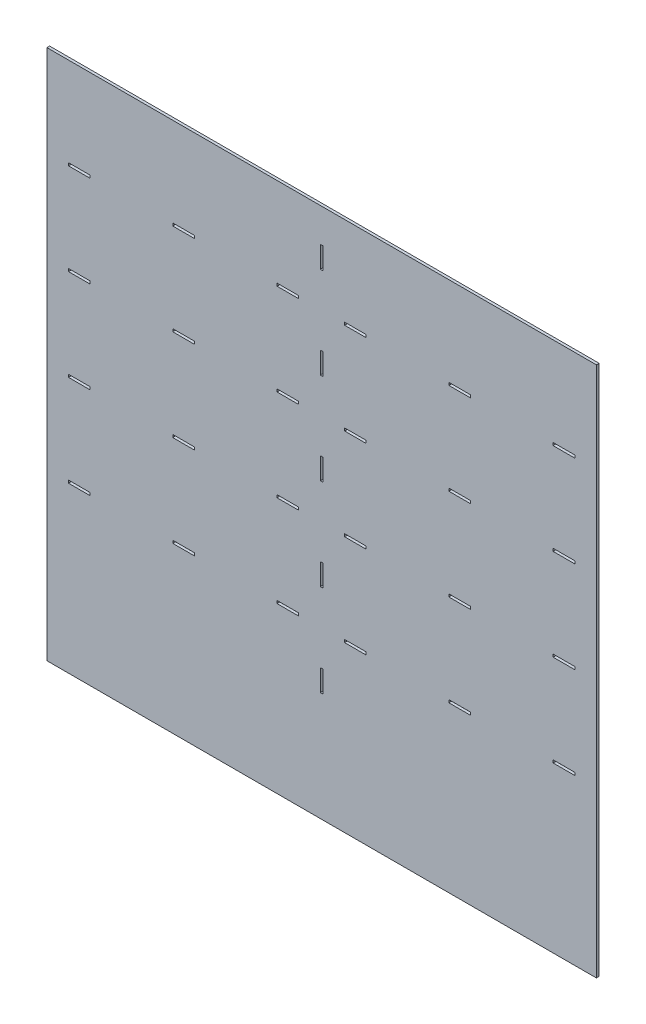
SolidWorks part; units mm, degrees
material "6061-T6 (SS)"
ref_plane "X-Y Datum" through (0, 0, 0) normal (0, 0, 1) x (1, 0, 0)
ref_plane "X-Z Datum" through (0, 0, 0) normal (0, 1, 0) x (1, 0, 0)
ref_plane "Y-Z Datum" through (0, 0, 0) normal (1, 0, 0) x (0, 0, -1)
sketch "Sketch1" plane through (0, 0, 0) normal (0, 0, 1) x (1, 0, 0)
  line L1 (0, 0) -> (314.2742, 0)
  line L2 (0, 0) -> (0, 86.4667)
  line L3 (0, 86.4667) -> (314.2742, 86.4667)
  line L4 (314.2742, 0) -> (314.2742, 86.4667)
  line L5 (0, 86.4667) -> (314.2742, 86.4667)
  line L6 (0, 86.4667) -> (0, 87.7367)
  line L7 (0, 87.7367) -> (314.2742, 87.7367)
  line L8 (314.2742, 86.4667) -> (314.2742, 87.7367)
  line L9 (0, 0) -> (314.2742, 0)
  line L10 (0, 0) -> (0, -1.27)
  line L11 (0, -1.27) -> (314.2742, -1.27)
  line L12 (314.2742, 0) -> (314.2742, -1.27)
  line L13 (0, 87.7367) -> (-1.27, 87.7367)
  line L14 (0, 87.7367) -> (0, -1.27)
  line L15 (0, -1.27) -> (-1.27, -1.27)
  line L16 (-1.27, 87.7367) -> (-1.27, -1.27)
  line L17 (314.2742, 87.7367) -> (315.5442, 87.7367)
  line L18 (314.2742, 87.7367) -> (314.2742, -1.27)
  line L19 (314.2742, -1.27) -> (315.5442, -1.27)
  line L20 (315.5442, 87.7367) -> (315.5442, -1.27)
  line L21 (-1.27, 87.7367) -> (-4.445, 87.7367)
  line L22 (-1.27, 87.7367) -> (-1.27, -1.27)
  line L23 (-1.27, -1.27) -> (-4.445, -1.27)
  line L24 (-4.445, 87.7367) -> (-4.445, -1.27)
  line L25 (-4.445, 87.7367) -> (-7.62, 87.7367)
  line L26 (-4.445, 87.7367) -> (-4.445, -1.27)
  line L27 (-4.445, -1.27) -> (-7.62, -1.27)
  line L28 (-7.62, 87.7367) -> (-7.62, -1.27)
  line L29 (315.5442, 87.7367) -> (318.7192, 87.7367)
  line L30 (315.5442, 87.7367) -> (315.5442, -1.27)
  line L31 (315.5442, -1.27) -> (318.7192, -1.27)
  line L32 (318.7192, 87.7367) -> (318.7192, -1.27)
  line L33 (318.7192, 87.7367) -> (321.8942, 87.7367)
  line L34 (318.7192, 87.7367) -> (318.7192, -1.27)
  line L35 (318.7192, -1.27) -> (321.8942, -1.27)
  line L36 (321.8942, 87.7367) -> (321.8942, -1.27)
  line L37 (-7.62, 87.7367) -> (321.8942, 87.7367)
  line L38 (-7.62, 87.7367) -> (-7.62, 90.9117)
  line L39 (-7.62, 90.9117) -> (321.8942, 90.9117)
  line L40 (321.8942, 87.7367) -> (321.8942, 90.9117)
  line L41 (-7.62, 90.9117) -> (321.8942, 90.9117)
  line L42 (-7.62, 90.9117) -> (-7.62, 94.0867)
  line L43 (-7.62, 94.0867) -> (321.8942, 94.0867)
  line L44 (321.8942, 90.9117) -> (321.8942, 94.0867)
  line L45 (-7.62, -1.27) -> (321.8942, -1.27)
  line L46 (-7.62, -1.27) -> (-7.62, -4.445)
  line L47 (-7.62, -4.445) -> (321.8942, -4.445)
  line L48 (321.8942, -1.27) -> (321.8942, -4.445)
  line L49 (321.8942, -4.445) -> (-7.62, -4.445)
  line L50 (321.8942, -4.445) -> (321.8942, -7.62)
  line L51 (321.8942, -7.62) -> (-7.62, -7.62)
  line L52 (-7.62, -4.445) -> (-7.62, -7.62)
  dimension "D1" = 314.2742
  dimension "D2" = 86.4667
  dimension "D3" = 1.27
  dimension "D4" = 1.27
  dimension "D5" = 1.27
  dimension "D6" = 1.27
  dimension "D7" = 3.175
  dimension "D8" = 3.175
  dimension "D9" = 3.175
  dimension "D10" = 3.175
  dimension "D11" = 3.175
  dimension "D12" = 3.175
  dimension "D13" = 3.175
  dimension "D14" = 3.175
sketch "Sketch4" plane through (0, 0, 0) normal (0, 0, 1) x (1, 0, 0)
  line L0 (-4.445, 87.7367) -> (-4.445, 90.9117) construction
  line L1 (-1.27, 87.7367) -> (315.5442, 87.7367)
  line L2 (-1.27, 87.7367) -> (-1.27, -1.27)
  line L3 (-1.27, -1.27) -> (315.5442, -1.27)
  line L4 (315.5442, 87.7367) -> (315.5442, -1.27)
  line L5 (-7.62, 90.9117) -> (321.8942, 90.9117) construction
  line L6 (318.7192, -1.27) -> (318.7192, -4.445) construction
  line L7 (-7.62, -4.445) -> (321.8942, -4.445) construction
  line L8 (-7.62, 92.4992) -> (-3.4571, 92.4992) construction
  line L9 (-4.445, 90.9117) -> (318.7192, 90.9117)
  line L10 (-4.445, 90.9117) -> (-4.445, -4.445)
  line L11 (-4.445, -4.445) -> (318.7192, -4.445)
  line L12 (318.7192, 90.9117) -> (318.7192, -4.445)
  line L14 (-1.27, 186.2684) -> (315.5442, 186.2684)
  line L15 (315.5442, 97.2617) -> (315.5442, 186.2684)
  line L16 (-1.27, 97.2617) -> (315.5442, 97.2617)
  line L17 (-1.27, 97.2617) -> (-1.27, 186.2684)
  line L18 (-4.445, 189.4434) -> (318.7192, 189.4434)
  line L19 (318.7192, 94.0867) -> (318.7192, 189.4434)
  line L20 (-4.445, 94.0867) -> (318.7192, 94.0867)
  line L21 (-4.445, 94.0867) -> (-4.445, 189.4434)
  line L22 (-4.445, 189.4434) -> (-4.445, 191.0309) construction
  line L23 (-4.445, 191.0309) -> (2.0975, 191.0309) construction
  line L24 (-1.27, 284.8) -> (-1.27, 195.7934)
  line L25 (-1.27, 284.8) -> (315.5442, 284.8)
  line L26 (315.5442, 284.8) -> (315.5442, 195.7934)
  line L27 (-1.27, 195.7934) -> (315.5442, 195.7934)
  line L28 (-4.445, 287.975) -> (-4.445, 192.6184)
  line L29 (-4.445, 287.975) -> (318.7192, 287.975)
  line L30 (318.7192, 287.975) -> (318.7192, 192.6184)
  line L31 (-4.445, 192.6184) -> (318.7192, 192.6184)
  line L32 (-4.445, 287.975) -> (-4.445, 289.5625) construction
  line L33 (-4.445, 289.5625) -> (-1.5046, 289.5625) construction
  line L34 (-1.27, 294.325) -> (315.5442, 294.325)
  line L35 (315.5442, 294.325) -> (315.5442, 383.3317)
  line L36 (-1.27, 383.3317) -> (315.5442, 383.3317)
  line L37 (-1.27, 294.325) -> (-1.27, 383.3317)
  line L38 (-4.445, 291.15) -> (318.7192, 291.15)
  line L39 (318.7192, 291.15) -> (318.7192, 386.5067)
  line L40 (-4.445, 386.5067) -> (318.7192, 386.5067)
  line L41 (-4.445, 291.15) -> (-4.445, 386.5067)
  line L42 (-4.445, 386.5067) -> (-4.445, 388.0942) construction
  line L43 (-4.445, 388.0942) -> (54.1144, 388.0942) construction
  line L44 (-1.27, 481.8634) -> (-1.27, 392.8567)
  line L45 (-1.27, 392.8567) -> (315.5442, 392.8567)
  line L46 (315.5442, 481.8634) -> (315.5442, 392.8567)
  line L47 (-1.27, 481.8634) -> (315.5442, 481.8634)
  line L48 (-4.445, 485.0384) -> (-4.445, 389.6817)
  line L49 (-4.445, 389.6817) -> (318.7192, 389.6817)
  line L50 (318.7192, 485.0384) -> (318.7192, 389.6817)
  line L51 (-4.445, 485.0384) -> (318.7192, 485.0384)
  line L52 (318.7192, -4.445) -> (320.3067, -4.445) construction
  line L53 (320.3067, -4.445) -> (320.3067, 0.7988) construction
  line L54 (641.8834, -1.27) -> (325.0692, -1.27)
  line L55 (325.0692, 87.7367) -> (325.0692, -1.27)
  line L56 (641.8834, 87.7367) -> (325.0692, 87.7367)
  line L57 (641.8834, 87.7367) -> (641.8834, -1.27)
  line L58 (645.0584, -4.445) -> (321.8942, -4.445)
  line L59 (321.8942, 90.9117) -> (321.8942, -4.445)
  line L60 (645.0584, 90.9117) -> (321.8942, 90.9117)
  line L61 (645.0584, 90.9117) -> (645.0584, -4.445)
  line L62 (641.8834, 97.2617) -> (641.8834, 186.2684)
  line L63 (641.8834, 97.2617) -> (325.0692, 97.2617)
  line L64 (325.0692, 97.2617) -> (325.0692, 186.2684)
  line L65 (641.8834, 186.2684) -> (325.0692, 186.2684)
  line L66 (645.0584, 94.0867) -> (645.0584, 189.4434)
  line L67 (645.0584, 94.0867) -> (321.8942, 94.0867)
  line L68 (321.8942, 94.0867) -> (321.8942, 189.4434)
  line L69 (645.0584, 189.4434) -> (321.8942, 189.4434)
  line L70 (641.8834, 284.8) -> (325.0692, 284.8)
  line L71 (325.0692, 284.8) -> (325.0692, 195.7934)
  line L72 (641.8834, 195.7934) -> (325.0692, 195.7934)
  line L73 (641.8834, 284.8) -> (641.8834, 195.7934)
  line L74 (645.0584, 287.975) -> (321.8942, 287.975)
  line L75 (321.8942, 287.975) -> (321.8942, 192.6184)
  line L76 (645.0584, 192.6184) -> (321.8942, 192.6184)
  line L77 (645.0584, 287.975) -> (645.0584, 192.6184)
  line L78 (641.8834, 294.325) -> (641.8834, 383.3317)
  line L79 (641.8834, 383.3317) -> (325.0692, 383.3317)
  line L80 (325.0692, 294.325) -> (325.0692, 383.3317)
  line L81 (641.8834, 294.325) -> (325.0692, 294.325)
  line L82 (645.0584, 291.15) -> (645.0584, 386.5067)
  line L83 (645.0584, 386.5067) -> (321.8942, 386.5067)
  line L84 (321.8942, 291.15) -> (321.8942, 386.5067)
  line L85 (645.0584, 291.15) -> (321.8942, 291.15)
  line L86 (641.8834, 481.8634) -> (325.0692, 481.8634)
  line L87 (325.0692, 481.8634) -> (325.0692, 392.8567)
  line L88 (641.8834, 392.8567) -> (325.0692, 392.8567)
  line L89 (641.8834, 481.8634) -> (641.8834, 392.8567)
  line L90 (645.0584, 485.0384) -> (321.8942, 485.0384)
  line L91 (321.8942, 485.0384) -> (321.8942, 389.6817)
  line L92 (645.0584, 389.6817) -> (321.8942, 389.6817)
  line L93 (645.0584, 485.0384) -> (645.0584, 389.6817)
sketch "Sketch5" plane through (0, 0, 0) normal (0, 0, 1) x (1, 0, 0)
  line L1 (-4.445, -4.445) -> (645.0584, -4.445)
  line L2 (-4.445, -4.445) -> (-4.445, 485.0384)
  line L3 (-4.445, 485.0384) -> (645.0584, 485.0384)
  line L4 (645.0584, -4.445) -> (645.0584, 485.0384)
  line L17 (-4.445, 240.2967) -> (411.848, 240.2967) construction
  line L18 (320.3067, -200004.445) -> (320.3067, 200000.7988) construction
  line L19 (318.7192, 227.5967) -> (321.8942, 227.5967)
  line L20 (318.7192, 227.5967) -> (318.7192, 252.9967)
  line L21 (318.7192, 252.9967) -> (321.8942, 252.9967)
  line L22 (321.8942, 227.5967) -> (321.8942, 252.9967)
  line L23 (318.7192, 227.5967) -> (321.8942, 252.9967) construction
  line L24 (318.7192, 252.9967) -> (321.8942, 227.5967) construction
  line L25 (321.8942, 287.975) -> (321.8942, 192.6184) construction
  line L26 (315.5442, 481.8634) -> (315.5442, 392.8567) construction
  line L27 (321.8942, 485.0384) -> (321.8942, 389.6817) construction
  line L28 (318.7192, 424.6601) -> (321.8942, 424.6601)
  line L29 (318.7192, 424.6601) -> (318.7192, 450.0601)
  line L30 (318.7192, 450.0601) -> (321.8942, 450.0601)
  line L31 (321.8942, 424.6601) -> (321.8942, 450.0601)
  line L32 (318.7192, 424.6601) -> (321.8942, 450.0601) construction
  line L33 (318.7192, 450.0601) -> (321.8942, 424.6601) construction
  line L34 (315.5442, 383.3317) -> (315.5442, 294.325) construction
  line L35 (321.8942, 291.15) -> (321.8942, 386.5067) construction
  line L36 (318.7192, 326.1284) -> (321.8942, 326.1284)
  line L37 (318.7192, 326.1284) -> (318.7192, 351.5284)
  line L38 (318.7192, 351.5284) -> (321.8942, 351.5284)
  line L39 (321.8942, 326.1284) -> (321.8942, 351.5284)
  line L40 (318.7192, 326.1284) -> (321.8942, 351.5284) construction
  line L41 (318.7192, 351.5284) -> (321.8942, 326.1284) construction
  line L42 (315.5442, 186.2684) -> (315.5442, 97.2617) construction
  line L44 (321.8942, 94.0867) -> (321.8942, 189.4434) construction
  line L45 (318.7192, 129.065) -> (321.8942, 129.065)
  line L46 (318.7192, 129.065) -> (318.7192, 154.465)
  line L47 (318.7192, 154.465) -> (321.8942, 154.465)
  line L48 (321.8942, 129.065) -> (321.8942, 154.465)
  line L49 (318.7192, 129.065) -> (321.8942, 154.465) construction
  line L50 (318.7192, 154.465) -> (321.8942, 129.065) construction
  line L51 (315.5442, 87.7367) -> (315.5442, -1.27) construction
  line L52 (321.8942, 90.9117) -> (321.8942, -4.445) construction
  line L53 (318.7192, 30.5333) -> (321.8942, 30.5333)
  line L54 (318.7192, 30.5333) -> (318.7192, 55.9333)
  line L55 (318.7192, 55.9333) -> (321.8942, 55.9333)
  line L56 (321.8942, 30.5333) -> (321.8942, 55.9333)
  line L57 (318.7192, 30.5333) -> (321.8942, 55.9333) construction
  line L58 (318.7192, 55.9333) -> (321.8942, 30.5333) construction
  line L59 (-4.445, 389.6817) -> (318.7192, 389.6817) construction
  line L60 (20.955, 389.6817) -> (46.355, 389.6817)
  line L61 (20.955, 389.6817) -> (20.955, 386.5067)
  line L62 (20.955, 386.5067) -> (46.355, 386.5067)
  line L63 (46.355, 389.6817) -> (46.355, 386.5067)
  line L64 (-4.445, 386.5067) -> (318.7192, 386.5067) construction
  line L65 (157.1371, 481.8634) -> (157.1371, -33.5321) construction
  line L66 (-1.27, 481.8634) -> (315.5442, 481.8634) construction
  line L67 (-4.445, 291.15) -> (318.7192, 291.15) construction
  line L68 (20.955, 291.15) -> (46.355, 291.15)
  line L69 (20.955, 291.15) -> (20.955, 287.975)
  line L70 (20.955, 287.975) -> (46.355, 287.975)
  line L71 (46.355, 291.15) -> (46.355, 287.975)
  line L72 (-4.445, 287.975) -> (318.7192, 287.975) construction
  line L73 (-4.445, 192.6184) -> (318.7192, 192.6184) construction
  line L74 (20.955, 192.6184) -> (46.355, 192.6184)
  line L75 (20.955, 192.6184) -> (20.955, 189.4434)
  line L76 (20.955, 189.4434) -> (46.355, 189.4434)
  line L77 (46.355, 192.6184) -> (46.355, 189.4434)
  line L78 (-4.445, 189.4434) -> (318.7192, 189.4434) construction
  line L79 (-4.445, 94.0867) -> (318.7192, 94.0867) construction
  line L80 (20.955, 94.0867) -> (46.355, 94.0867)
  line L81 (20.955, 94.0867) -> (20.955, 90.9117)
  line L82 (20.955, 90.9117) -> (46.355, 90.9117)
  line L83 (46.355, 94.0867) -> (46.355, 90.9117)
  line L84 (-4.445, 90.9117) -> (318.7192, 90.9117) construction
  line L85 (293.3192, 90.9117) -> (267.9192, 90.9117)
  line L86 (267.9192, 94.0867) -> (267.9192, 90.9117)
  line L87 (293.3192, 94.0867) -> (267.9192, 94.0867)
  line L88 (293.3192, 94.0867) -> (293.3192, 90.9117)
  line L89 (293.3192, 189.4434) -> (267.9192, 189.4434)
  line L90 (267.9192, 192.6184) -> (267.9192, 189.4434)
  line L91 (293.3192, 192.6184) -> (267.9192, 192.6184)
  line L92 (293.3192, 192.6184) -> (293.3192, 189.4434)
  line L93 (293.3192, 287.975) -> (267.9192, 287.975)
  line L94 (267.9192, 291.15) -> (267.9192, 287.975)
  line L95 (293.3192, 291.15) -> (267.9192, 291.15)
  line L96 (293.3192, 291.15) -> (293.3192, 287.975)
  line L97 (293.3192, 386.5067) -> (267.9192, 386.5067)
  line L98 (267.9192, 389.6817) -> (267.9192, 386.5067)
  line L99 (293.3192, 389.6817) -> (267.9192, 389.6817)
  line L100 (293.3192, 389.6817) -> (293.3192, 386.5067)
  line L101 (-200004.445, 388.0942) -> (200054.1144, 388.0942) construction
  line L102 (144.4371, 386.5067) -> (169.8371, 386.5067)
  line L103 (144.4371, 386.5067) -> (144.4371, 389.6817)
  line L104 (144.4371, 389.6817) -> (169.8371, 389.6817)
  line L105 (169.8371, 386.5067) -> (169.8371, 389.6817)
  line L106 (144.4371, 386.5067) -> (169.8371, 389.6817) construction
  line L107 (144.4371, 389.6817) -> (169.8371, 386.5067) construction
  line L108 (-200007.62, 92.4992) -> (199996.5429, 92.4992) construction
  line L109 (144.4371, 287.9943) -> (169.8371, 287.9943)
  line L110 (144.4371, 287.9943) -> (144.4371, 291.15)
  line L111 (144.4371, 291.15) -> (169.8371, 291.15)
  line L112 (169.8371, 287.9943) -> (169.8371, 291.15)
  line L113 (144.4371, 287.9943) -> (169.8371, 291.15) construction
  line L114 (144.4371, 291.15) -> (169.8371, 287.9943) construction
  line L115 (144.4371, 189.7684) -> (169.8371, 189.7684)
  line L116 (144.4371, 189.7684) -> (144.4371, 192.6184)
  line L117 (144.4371, 192.6184) -> (169.8371, 192.6184)
  line L118 (169.8371, 189.7684) -> (169.8371, 192.6184)
  line L119 (144.4371, 189.7684) -> (169.8371, 192.6184) construction
  line L120 (144.4371, 192.6184) -> (169.8371, 189.7684) construction
  line L121 (144.4371, 90.0322) -> (169.8371, 90.0322)
  line L122 (144.4371, 90.0322) -> (144.4371, 94.9661)
  line L123 (144.4371, 94.9661) -> (169.8371, 94.9661)
  line L124 (169.8371, 90.0322) -> (169.8371, 94.9661)
  line L125 (144.4371, 90.0322) -> (169.8371, 94.9661) construction
  line L126 (144.4371, 94.9661) -> (169.8371, 90.0322) construction
  line L127 (320.3067, 527.3775) -> (320.3067, -150.1423) construction
  line L128 (619.6584, 90.9117) -> (594.2584, 90.9117)
  line L129 (594.2584, 94.0867) -> (594.2584, 90.9117)
  line L130 (619.6584, 94.0867) -> (594.2584, 94.0867)
  line L131 (619.6584, 94.0867) -> (619.6584, 90.9117)
  line L132 (496.1763, 94.9661) -> (470.7763, 94.9661)
  line L133 (470.7763, 90.0322) -> (470.7763, 94.9661)
  line L134 (496.1763, 90.0322) -> (470.7763, 90.0322)
  line L135 (496.1763, 90.0322) -> (496.1763, 94.9661)
  line L136 (347.2942, 94.0867) -> (347.2942, 90.9117)
  line L137 (347.2942, 94.0867) -> (372.6942, 94.0867)
  line L138 (372.6942, 94.0867) -> (372.6942, 90.9117)
  line L139 (347.2942, 90.9117) -> (372.6942, 90.9117)
  line L140 (347.2942, 192.6184) -> (347.2942, 189.4434)
  line L141 (347.2942, 192.6184) -> (372.6942, 192.6184)
  line L142 (372.6942, 192.6184) -> (372.6942, 189.4434)
  line L143 (347.2942, 189.4434) -> (372.6942, 189.4434)
  line L144 (496.1763, 192.6184) -> (470.7763, 192.6184)
  line L145 (470.7763, 189.7684) -> (470.7763, 192.6184)
  line L146 (496.1763, 189.7684) -> (470.7763, 189.7684)
  line L147 (496.1763, 189.7684) -> (496.1763, 192.6184)
  line L148 (619.6584, 189.4434) -> (594.2584, 189.4434)
  line L149 (594.2584, 192.6184) -> (594.2584, 189.4434)
  line L150 (619.6584, 192.6184) -> (594.2584, 192.6184)
  line L151 (619.6584, 192.6184) -> (619.6584, 189.4434)
  line L152 (619.6584, 287.975) -> (594.2584, 287.975)
  line L153 (594.2584, 291.15) -> (594.2584, 287.975)
  line L154 (619.6584, 291.15) -> (594.2584, 291.15)
  line L155 (619.6584, 291.15) -> (619.6584, 287.975)
  line L156 (496.1763, 291.15) -> (470.7763, 291.15)
  line L157 (470.7763, 287.9943) -> (470.7763, 291.15)
  line L158 (496.1763, 287.9943) -> (470.7763, 287.9943)
  line L159 (496.1763, 287.9943) -> (496.1763, 291.15)
  line L160 (347.2942, 291.15) -> (347.2942, 287.975)
  line L161 (347.2942, 291.15) -> (372.6942, 291.15)
  line L162 (372.6942, 291.15) -> (372.6942, 287.975)
  line L163 (347.2942, 287.975) -> (372.6942, 287.975)
  line L164 (347.2942, 389.6817) -> (347.2942, 386.5067)
  line L165 (347.2942, 389.6817) -> (372.6942, 389.6817)
  line L166 (372.6942, 389.6817) -> (372.6942, 386.5067)
  line L167 (347.2942, 386.5067) -> (372.6942, 386.5067)
  line L168 (496.1763, 389.6817) -> (470.7763, 389.6817)
  line L169 (470.7763, 386.5067) -> (470.7763, 389.6817)
  line L170 (496.1763, 386.5067) -> (470.7763, 386.5067)
  line L171 (496.1763, 386.5067) -> (496.1763, 389.6817)
  line L172 (619.6584, 386.5067) -> (594.2584, 386.5067)
  line L173 (594.2584, 389.6817) -> (594.2584, 386.5067)
  line L174 (619.6584, 389.6817) -> (594.2584, 389.6817)
  line L175 (619.6584, 389.6817) -> (619.6584, 386.5067)
  point P8 (320.3067, 43.2333)
  point P12 (320.3067, 437.3601)
  point P24 (320.3067, 240.2967)
  point P40 (320.3067, 338.8284)
  point P53 (320.3067, 141.765)
  point P113 (157.1371, 388.0942)
  point P120 (157.1371, 289.5722)
  point P125 (157.1371, 191.1934)
  point P130 (157.1371, 92.4992)
  dimension "D1" = 25.4
  dimension "D2" = 25.4
  dimension "D3" = 25.4
  dimension "D4" = 25.4
  dimension "D5" = 25.4
  dimension "D6" = 25.4
  dimension "D7" = 25.4
  dimension "D8" = 25.4
sketch "Sketch7" plane through (0, 0, 0) normal (0, 0, 1) x (1, 0, 0)
  line L0 (-2.032, 422.1632) -> (-2.032, 423.7507) construction
  line L5 (-2.032, -2.032) -> (-2.032, 96.0704)
  line L10 (0, 0) -> (310.8274, 0)
  line L11 (0, 0) -> (0, 94.0384)
  line L12 (0, 94.0384) -> (310.8274, 94.0384)
  line L13 (310.8274, 0) -> (310.8274, 94.0384)
  line L14 (-2.032, 96.0704) -> (312.8594, 96.0704)
  line L15 (312.8594, -2.032) -> (312.8594, 96.0704)
  line L16 (-2.032, -2.032) -> (312.8594, -2.032)
  line L17 (-5.207, 99.2454) -> (316.0344, 99.2454)
  line L18 (316.0344, -5.207) -> (316.0344, 99.2454)
  line L19 (-5.207, -5.207) -> (316.0344, -5.207)
  line L20 (-5.207, -5.207) -> (-5.207, 99.2454)
  line L21 (-5.207, 99.2454) -> (-5.207, 100.8507) construction
  line L22 (-5.207, 100.8507) -> (332.9978, 100.8507) construction
  line L23 (-2.032, 203.7334) -> (312.8594, 203.7334)
  line L24 (312.8594, 203.7334) -> (312.8594, 105.631)
  line L25 (-2.032, 105.631) -> (312.8594, 105.631)
  line L26 (-2.032, 203.7334) -> (-2.032, 105.631)
  line L27 (0, 107.663) -> (310.8274, 107.663)
  line L28 (310.8274, 201.7014) -> (310.8274, 107.663)
  line L29 (0, 201.7014) -> (310.8274, 201.7014)
  line L30 (0, 201.7014) -> (0, 107.663)
  line L31 (-5.207, 206.9084) -> (-5.207, 102.456)
  line L32 (-5.207, 206.9084) -> (316.0344, 206.9084)
  line L33 (316.0344, 206.9084) -> (316.0344, 102.456)
  line L34 (-5.207, 102.456) -> (316.0344, 102.456)
  line L35 (-5.207, 206.9084) -> (-5.207, 208.4959) construction
  line L36 (-5.207, 208.4959) -> (6.6362, 208.4959) construction
  line L37 (-2.032, 213.2584) -> (-2.032, 311.3608)
  line L38 (-2.032, 311.3608) -> (312.8594, 311.3608)
  line L39 (312.8594, 213.2584) -> (312.8594, 311.3608)
  line L40 (-2.032, 213.2584) -> (312.8594, 213.2584)
  line L41 (0, 215.2904) -> (0, 309.3288)
  line L42 (0, 215.2904) -> (310.8274, 215.2904)
  line L43 (310.8274, 215.2904) -> (310.8274, 309.3288)
  line L44 (0, 309.3288) -> (310.8274, 309.3288)
  line L45 (-5.207, 210.0834) -> (316.0344, 210.0834)
  line L46 (316.0344, 210.0834) -> (316.0344, 314.5358)
  line L47 (-5.207, 314.5358) -> (316.0344, 314.5358)
  line L48 (-5.207, 210.0834) -> (-5.207, 314.5358)
  line L49 (-3.3313, 314.5358) -> (-3.3313, 316.1233) construction
  line L50 (-8.425, 316.1233) -> (12.0376, 316.1233) construction
  line L51 (0, 416.9562) -> (310.8274, 416.9562)
  line L52 (310.8274, 416.9562) -> (310.8274, 322.9178)
  line L53 (0, 322.9178) -> (310.8274, 322.9178)
  line L54 (0, 416.9562) -> (0, 322.9178)
  line L55 (-2.032, 418.9882) -> (312.8594, 418.9882)
  line L56 (312.8594, 418.9882) -> (312.8594, 320.8858)
  line L57 (-2.032, 320.8858) -> (312.8594, 320.8858)
  line L58 (-2.032, 418.9882) -> (-2.032, 320.8858)
  line L59 (-5.207, 422.1632) -> (-5.207, 317.7108)
  line L60 (-5.207, 317.7108) -> (316.0344, 317.7108)
  line L61 (316.0344, 422.1632) -> (316.0344, 317.7108)
  line L62 (-5.207, 422.1632) -> (316.0344, 422.1632)
  line L63 (-10.8123, 423.7507) -> (13.1304, 423.7507) construction
  line L64 (0, 430.5452) -> (0, 524.5837)
  line L65 (0, 524.5837) -> (310.8274, 524.5837)
  line L66 (310.8274, 430.5452) -> (310.8274, 524.5837)
  line L67 (0, 430.5452) -> (310.8274, 430.5452)
  line L68 (-2.032, 428.5132) -> (-2.032, 526.6157)
  line L69 (-2.032, 526.6157) -> (312.8594, 526.6157)
  line L70 (312.8594, 428.5132) -> (312.8594, 526.6157)
  line L71 (-2.032, 428.5132) -> (312.8594, 428.5132)
  line L72 (-5.207, 425.3382) -> (316.0344, 425.3382)
  line L73 (316.0344, 425.3382) -> (316.0344, 529.7907)
  line L74 (-5.207, 529.7907) -> (316.0344, 529.7907)
  line L75 (-5.207, 425.3382) -> (-5.207, 529.7907)
  line L76 (316.0344, 529.7907) -> (317.6219, 529.7907) construction
  line L77 (317.6219, 529.7907) -> (317.6219, 523.6304) construction
  line L78 (635.2438, 94.0384) -> (324.4164, 94.0384)
  line L79 (324.4164, 0) -> (324.4164, 94.0384)
  line L80 (635.2438, 0) -> (324.4164, 0)
  line L81 (635.2438, 0) -> (635.2438, 94.0384)
  line L82 (637.2758, -2.032) -> (322.3844, -2.032)
  line L83 (322.3844, -2.032) -> (322.3844, 96.0704)
  line L84 (637.2758, 96.0704) -> (322.3844, 96.0704)
  line L85 (637.2758, -2.032) -> (637.2758, 96.0704)
  line L86 (640.4508, -5.207) -> (640.4508, 99.2454)
  line L87 (640.4508, -5.207) -> (319.2094, -5.207)
  line L88 (319.2094, -5.207) -> (319.2094, 99.2454)
  line L89 (640.4508, 99.2454) -> (319.2094, 99.2454)
  line L90 (635.2438, 201.7014) -> (635.2438, 107.663)
  line L91 (635.2438, 201.7014) -> (324.4164, 201.7014)
  line L92 (324.4164, 201.7014) -> (324.4164, 107.663)
  line L93 (635.2438, 107.663) -> (324.4164, 107.663)
  line L94 (637.2758, 203.7334) -> (637.2758, 105.631)
  line L95 (637.2758, 105.631) -> (322.3844, 105.631)
  line L96 (322.3844, 203.7334) -> (322.3844, 105.631)
  line L97 (637.2758, 203.7334) -> (322.3844, 203.7334)
  line L98 (640.4508, 206.9084) -> (319.2094, 206.9084)
  line L99 (319.2094, 206.9084) -> (319.2094, 102.456)
  line L100 (640.4508, 102.456) -> (319.2094, 102.456)
  line L101 (640.4508, 206.9084) -> (640.4508, 102.456)
  line L102 (635.2438, 215.2904) -> (324.4164, 215.2904)
  line L103 (324.4164, 215.2904) -> (324.4164, 309.3288)
  line L104 (635.2438, 309.3288) -> (324.4164, 309.3288)
  line L105 (635.2438, 215.2904) -> (635.2438, 309.3288)
  line L106 (637.2758, 213.2584) -> (322.3844, 213.2584)
  line L107 (322.3844, 213.2584) -> (322.3844, 311.3608)
  line L108 (637.2758, 311.3608) -> (322.3844, 311.3608)
  line L109 (637.2758, 213.2584) -> (637.2758, 311.3608)
  line L110 (640.4508, 210.0834) -> (640.4508, 314.5358)
  line L111 (640.4508, 314.5358) -> (319.2094, 314.5358)
  line L112 (319.2094, 210.0834) -> (319.2094, 314.5358)
  line L113 (640.4508, 210.0834) -> (319.2094, 210.0834)
  line L114 (635.2438, 416.9562) -> (635.2438, 322.9178)
  line L115 (635.2438, 322.9178) -> (324.4164, 322.9178)
  line L116 (324.4164, 416.9562) -> (324.4164, 322.9178)
  line L117 (635.2438, 416.9562) -> (324.4164, 416.9562)
  line L118 (637.2758, 418.9882) -> (637.2758, 320.8858)
  line L119 (637.2758, 320.8858) -> (322.3844, 320.8858)
  line L120 (322.3844, 418.9882) -> (322.3844, 320.8858)
  line L121 (637.2758, 418.9882) -> (322.3844, 418.9882)
  line L122 (640.4508, 422.1632) -> (319.2094, 422.1632)
  line L123 (319.2094, 422.1632) -> (319.2094, 317.7108)
  line L124 (640.4508, 317.7108) -> (319.2094, 317.7108)
  line L125 (640.4508, 422.1632) -> (640.4508, 317.7108)
  line L126 (635.2438, 430.5452) -> (324.4164, 430.5452)
  line L127 (324.4164, 430.5452) -> (324.4164, 524.5837)
  line L128 (635.2438, 524.5837) -> (324.4164, 524.5837)
  line L129 (635.2438, 430.5452) -> (635.2438, 524.5837)
  line L130 (637.2758, 428.5132) -> (322.3844, 428.5132)
  line L131 (322.3844, 428.5132) -> (322.3844, 526.6157)
  line L132 (637.2758, 526.6157) -> (322.3844, 526.6157)
  line L133 (637.2758, 428.5132) -> (637.2758, 526.6157)
  line L134 (640.4508, 425.3382) -> (640.4508, 529.7907)
  line L135 (640.4508, 529.7907) -> (319.2094, 529.7907)
  line L136 (319.2094, 425.3382) -> (319.2094, 529.7907)
  line L137 (640.4508, 425.3382) -> (319.2094, 425.3382)
  dimension "D1" = 310.8274
  dimension "D2" = 94.0384
  dimension "D3" = 2.032
  dimension "D4" = 3.175
sketch "Sketch8" plane through (0, 0, 0) normal (0, 0, 1) x (1, 0, 0)
  line L0 (310.8274, 524.5837) -> (310.8274, 430.5452) construction
  line L1 (-5.207, -5.207) -> (640.4508, -5.207)
  line L2 (-5.207, -5.207) -> (-5.207, 529.7907)
  line L3 (-5.207, 529.7907) -> (640.4508, 529.7907)
  line L4 (640.4508, -5.207) -> (640.4508, 529.7907)
  line L5 (317.6219, 200529.7907) -> (317.6219, -199476.3696) construction
  line L6 (316.0344, 464.8644) -> (319.2094, 464.8644)
  line L7 (316.0344, 464.8644) -> (316.0344, 490.2644)
  line L8 (316.0344, 490.2644) -> (319.2094, 490.2644)
  line L9 (319.2094, 464.8644) -> (319.2094, 490.2644)
  line L10 (316.0344, 464.8644) -> (319.2094, 490.2644) construction
  line L11 (316.0344, 490.2644) -> (319.2094, 464.8644) construction
  line L12 (319.2094, 425.3382) -> (319.2094, 529.7907) construction
  line L13 (319.2094, 422.1632) -> (319.2094, 317.7108) construction
  line L14 (316.0344, 357.237) -> (319.2094, 357.237)
  line L15 (316.0344, 357.237) -> (316.0344, 382.637)
  line L16 (316.0344, 382.637) -> (319.2094, 382.637)
  line L17 (319.2094, 357.237) -> (319.2094, 382.637)
  line L18 (316.0344, 357.237) -> (319.2094, 382.637) construction
  line L19 (316.0344, 382.637) -> (319.2094, 357.237) construction
  line L20 (319.2094, 210.0834) -> (319.2094, 314.5358) construction
  line L21 (316.0344, 249.7583) -> (319.2094, 249.7583)
  line L22 (316.0344, 249.7583) -> (316.0344, 275.1583)
  line L23 (316.0344, 275.1583) -> (319.2094, 275.1583)
  line L24 (319.2094, 249.7583) -> (319.2094, 275.1583)
  line L25 (316.0344, 249.7583) -> (319.2094, 275.1583) construction
  line L26 (316.0344, 275.1583) -> (319.2094, 249.7583) construction
  line L27 (319.2094, 206.9084) -> (319.2094, 102.456) construction
  line L28 (316.0344, 141.982) -> (319.2094, 141.982)
  line L29 (316.0344, 141.982) -> (316.0344, 167.382)
  line L30 (316.0344, 167.382) -> (319.2094, 167.382)
  line L31 (319.2094, 141.982) -> (319.2094, 167.382)
  line L32 (316.0344, 141.982) -> (319.2094, 167.382) construction
  line L33 (316.0344, 167.382) -> (319.2094, 141.982) construction
  line L34 (319.2094, -5.207) -> (319.2094, 99.2454) construction
  line L35 (316.0344, 34.1911) -> (319.2094, 34.1911)
  line L36 (316.0344, 34.1911) -> (316.0344, 59.5911)
  line L37 (316.0344, 59.5911) -> (319.2094, 59.5911)
  line L38 (319.2094, 34.1911) -> (319.2094, 59.5911)
  line L39 (316.0344, 34.1911) -> (319.2094, 59.5911) construction
  line L40 (316.0344, 59.5911) -> (319.2094, 34.1911) construction
  line L41 (-5.207, 425.3382) -> (316.0344, 425.3382) construction
  line L42 (20.193, 425.3382) -> (45.593, 425.3382)
  line L43 (20.193, 425.3382) -> (20.193, 422.1632)
  line L44 (20.193, 422.1632) -> (45.593, 422.1632)
  line L45 (45.593, 425.3382) -> (45.593, 422.1632)
  line L46 (-5.207, 422.1632) -> (316.0344, 422.1632) construction
  line L47 (155.4137, 524.5837) -> (155.4137, -61.488) construction
  line L49 (-200010.8123, 423.7507) -> (200013.1304, 423.7507) construction
  line L50 (142.7137, 422.1632) -> (168.1137, 422.1632)
  line L51 (142.7137, 422.1632) -> (142.7137, 425.3382)
  line L52 (142.7137, 425.3382) -> (168.1137, 425.3382)
  line L53 (168.1137, 422.1632) -> (168.1137, 425.3382)
  line L54 (142.7137, 422.1632) -> (168.1137, 425.3382) construction
  line L55 (142.7137, 425.3382) -> (168.1137, 422.1632) construction
  line L56 (-5.207, 317.7108) -> (316.0344, 317.7108) construction
  line L57 (20.193, 317.7108) -> (45.593, 317.7108)
  line L58 (20.193, 317.7108) -> (20.193, 314.5358)
  line L59 (20.193, 314.5358) -> (45.593, 314.5358)
  line L60 (45.593, 317.7108) -> (45.593, 314.5358)
  line L61 (-5.207, 314.5358) -> (316.0344, 314.5358) construction
  line L62 (-5.207, 210.0834) -> (316.0344, 210.0834) construction
  line L63 (20.193, 210.0834) -> (45.593, 210.0834)
  line L64 (20.193, 210.0834) -> (20.193, 206.9084)
  line L65 (20.193, 206.9084) -> (45.593, 206.9084)
  line L66 (45.593, 210.0834) -> (45.593, 206.9084)
  line L67 (-5.207, 206.9084) -> (316.0344, 206.9084) construction
  line L68 (-5.207, 102.456) -> (316.0344, 102.456) construction
  line L69 (20.193, 102.456) -> (45.593, 102.456)
  line L70 (20.193, 102.456) -> (20.193, 99.2454)
  line L71 (20.193, 99.2454) -> (45.593, 99.2454)
  line L72 (45.593, 102.456) -> (45.593, 99.2454)
  line L73 (-5.207, 99.2454) -> (316.0344, 99.2454) construction
  line L74 (290.6344, 422.1632) -> (265.2344, 422.1632)
  line L75 (142.7137, 317.7108) -> (168.1137, 317.7108)
  line L76 (142.7137, 317.7108) -> (142.7137, 314.5358)
  line L77 (142.7137, 314.5358) -> (168.1137, 314.5358)
  line L78 (168.1137, 317.7108) -> (168.1137, 314.5358)
  line L79 (142.7137, 210.0834) -> (168.1137, 210.0834)
  line L80 (142.7137, 210.0834) -> (142.7137, 206.9084)
  line L81 (142.7137, 206.9084) -> (168.1137, 206.9084)
  line L82 (168.1137, 210.0834) -> (168.1137, 206.9084)
  line L83 (142.7137, 102.456) -> (168.1137, 102.456)
  line L84 (142.7137, 102.456) -> (142.7137, 99.2454)
  line L85 (142.7137, 99.2454) -> (168.1137, 99.2454)
  line L86 (168.1137, 102.456) -> (168.1137, 99.2454)
  line L87 (265.2344, 425.3382) -> (265.2344, 422.1632)
  line L88 (290.6344, 425.3382) -> (265.2344, 425.3382)
  line L89 (290.6344, 425.3382) -> (290.6344, 422.1632)
  line L90 (290.6344, 314.5358) -> (265.2344, 314.5358)
  line L91 (265.2344, 317.7108) -> (265.2344, 314.5358)
  line L92 (290.6344, 317.7108) -> (265.2344, 317.7108)
  line L93 (290.6344, 317.7108) -> (290.6344, 314.5358)
  line L94 (290.6344, 206.9084) -> (265.2344, 206.9084)
  line L95 (265.2344, 210.0834) -> (265.2344, 206.9084)
  line L96 (290.6344, 210.0834) -> (265.2344, 210.0834)
  line L97 (290.6344, 210.0834) -> (290.6344, 206.9084)
  line L98 (290.6344, 99.2454) -> (265.2344, 99.2454)
  line L99 (265.2344, 102.456) -> (265.2344, 99.2454)
  line L100 (290.6344, 102.456) -> (265.2344, 102.456)
  line L101 (290.6344, 102.456) -> (290.6344, 99.2454)
  line L102 (317.6219, 753.6072) -> (317.6219, -220.7674) construction
  line L103 (615.0508, 99.2454) -> (589.6508, 99.2454)
  line L104 (589.6508, 102.456) -> (589.6508, 99.2454)
  line L105 (615.0508, 102.456) -> (589.6508, 102.456)
  line L106 (615.0508, 102.456) -> (615.0508, 99.2454)
  line L107 (492.5301, 99.2454) -> (467.1301, 99.2454)
  line L108 (467.1301, 102.456) -> (467.1301, 99.2454)
  line L109 (492.5301, 102.456) -> (467.1301, 102.456)
  line L110 (492.5301, 102.456) -> (492.5301, 99.2454)
  line L111 (344.6094, 102.456) -> (344.6094, 99.2454)
  line L112 (344.6094, 102.456) -> (370.0094, 102.456)
  line L113 (370.0094, 102.456) -> (370.0094, 99.2454)
  line L114 (344.6094, 99.2454) -> (370.0094, 99.2454)
  line L115 (344.6094, 210.0834) -> (344.6094, 206.9084)
  line L116 (344.6094, 210.0834) -> (370.0094, 210.0834)
  line L117 (370.0094, 210.0834) -> (370.0094, 206.9084)
  line L118 (344.6094, 206.9084) -> (370.0094, 206.9084)
  line L119 (492.5301, 206.9084) -> (467.1301, 206.9084)
  line L120 (467.1301, 210.0834) -> (467.1301, 206.9084)
  line L121 (492.5301, 210.0834) -> (467.1301, 210.0834)
  line L122 (492.5301, 210.0834) -> (492.5301, 206.9084)
  line L123 (615.0508, 206.9084) -> (589.6508, 206.9084)
  line L124 (589.6508, 210.0834) -> (589.6508, 206.9084)
  line L125 (615.0508, 210.0834) -> (589.6508, 210.0834)
  line L126 (615.0508, 210.0834) -> (615.0508, 206.9084)
  line L127 (615.0508, 314.5358) -> (589.6508, 314.5358)
  line L128 (589.6508, 317.7108) -> (589.6508, 314.5358)
  line L129 (615.0508, 317.7108) -> (589.6508, 317.7108)
  line L130 (615.0508, 317.7108) -> (615.0508, 314.5358)
  line L131 (492.5301, 314.5358) -> (467.1301, 314.5358)
  line L132 (467.1301, 317.7108) -> (467.1301, 314.5358)
  line L133 (492.5301, 317.7108) -> (467.1301, 317.7108)
  line L134 (492.5301, 317.7108) -> (492.5301, 314.5358)
  line L135 (344.6094, 317.7108) -> (344.6094, 314.5358)
  line L136 (344.6094, 317.7108) -> (370.0094, 317.7108)
  line L137 (370.0094, 317.7108) -> (370.0094, 314.5358)
  line L138 (344.6094, 314.5358) -> (370.0094, 314.5358)
  line L139 (344.6094, 425.3382) -> (344.6094, 422.1632)
  line L140 (344.6094, 425.3382) -> (370.0094, 425.3382)
  line L141 (370.0094, 425.3382) -> (370.0094, 422.1632)
  line L142 (344.6094, 422.1632) -> (370.0094, 422.1632)
  line L143 (492.5301, 425.3382) -> (467.1301, 425.3382)
  line L144 (467.1301, 422.1632) -> (467.1301, 425.3382)
  line L145 (492.5301, 422.1632) -> (467.1301, 422.1632)
  line L146 (492.5301, 422.1632) -> (492.5301, 425.3382)
  line L147 (615.0508, 422.1632) -> (589.6508, 422.1632)
  line L148 (589.6508, 425.3382) -> (589.6508, 422.1632)
  line L149 (615.0508, 425.3382) -> (589.6508, 425.3382)
  line L150 (615.0508, 425.3382) -> (615.0508, 422.1632)
  point P10 (317.6219, 477.5644)
  point P19 (317.6219, 369.937)
  point P26 (317.6219, 262.4583)
  point P33 (317.6219, 154.682)
  point P40 (317.6219, 46.8911)
  point P57 (155.4137, 423.7507)
  dimension "D1" = 25.4
  dimension "D2" = 25.4
  dimension "D3" = 25.4
  dimension "D4" = 25.4
  dimension "D5" = 25.4
  dimension "D6" = 25.4
  dimension "D7" = 25.4
  dimension "D8" = 25.4
extrude "Boss-Extrude2" add sketch "Sketch8" along normal blind 3.175
sketch "Sketch9" plane through (0, 0, 3.175) normal (0, 0, 1) x (1, 0, 0)
  line L18 (-5.207, 529.7907) -> (169.2364, 529.7907)
  line L19 (-5.207, 529.7907) -> (-5.207, 566.6207)
  line L20 (-5.207, 566.6207) -> (169.2364, 566.6207)
  line L21 (169.2364, 529.7907) -> (169.2364, 566.6207)
  line L26 (640.4508, 529.7907) -> (514.9965, 529.7907)
  line L27 (640.4508, 529.7907) -> (640.4508, 566.6207)
  line L28 (640.4508, 566.6207) -> (514.9965, 566.6207)
  line L29 (514.9965, 529.7907) -> (514.9965, 566.6207)
  line L30 (-5.207, -5.207) -> (-42.037, -5.207)
  line L31 (-5.207, -5.207) -> (-5.207, 98.1058)
  line L32 (-5.207, 98.1058) -> (-42.037, 98.1058)
  line L33 (-42.037, -5.207) -> (-42.037, 98.1058)
  line L34 (640.4508, -5.207) -> (677.2808, -5.207)
  line L35 (640.4508, -5.207) -> (640.4508, 90.7799)
  line L36 (640.4508, 90.7799) -> (677.2808, 90.7799)
  line L37 (677.2808, -5.207) -> (677.2808, 90.7799)
extrude "Boss-Extrude3" [suppressed] add sketch "Sketch9" against normal through all
sketch "Sketch10" plane through (0, 0, 3.175) normal (0, 0, 1) x (1, 0, 0)
  line L5 (-5.207, -5.207) -> (640.4508, -5.207)
  line L6 (-5.207, -5.207) -> (-5.207, -94.107)
  line L7 (-5.207, -94.107) -> (640.4508, -94.107)
  line L8 (640.4508, -5.207) -> (640.4508, -94.107)
extrude "Boss-Extrude6" add sketch "Sketch10" against normal through all
